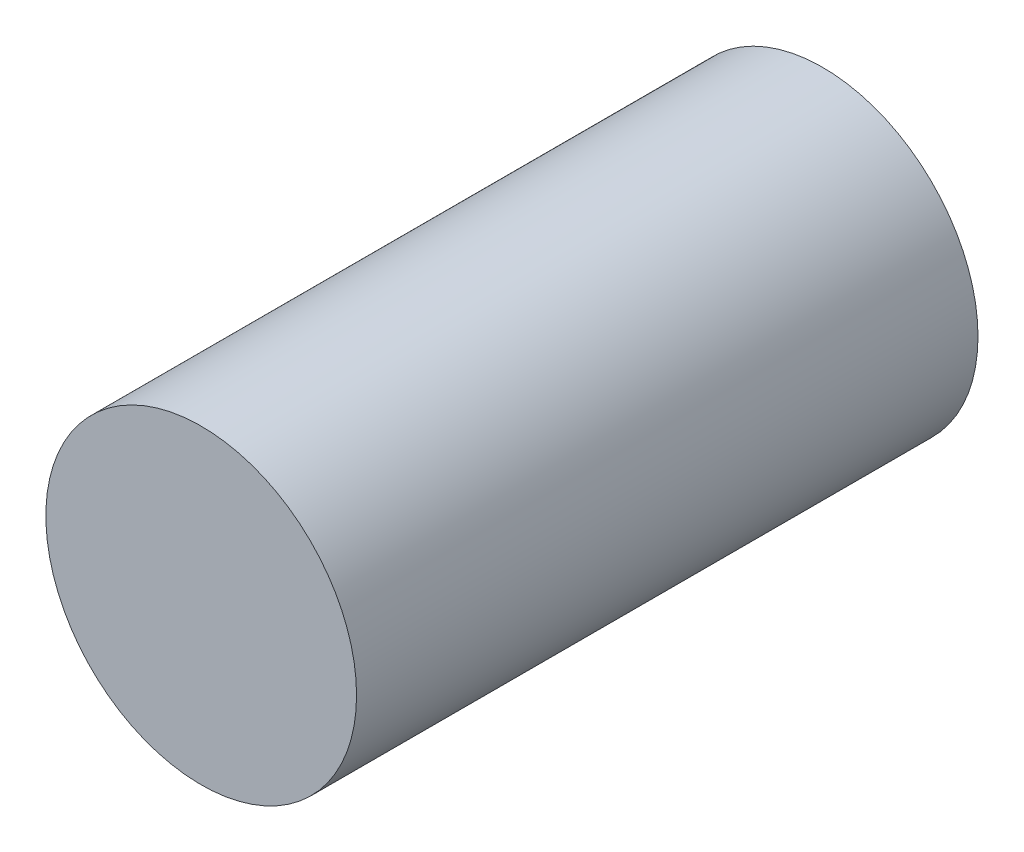
SolidWorks part; units mm, degrees
material "ABS PC"
ref_plane "Front Plane" through (0, 0, 0) normal (0, 0, 1) x (1, 0, 0)
ref_plane "Top Plane" through (0, 0, 0) normal (0, 1, 0) x (1, 0, 0)
ref_plane "Right Plane" through (0, 0, 0) normal (1, 0, 0) x (0, 0, -1)
sketch "Sketch1" plane through (0, 0, 0) normal (0, 0, 1) x (1, 0, 0)
  circle A0 centre (0, 0) radius 1.5875
  dimension "D1" = 3.175
extrude "Boss-Extrude1" add sketch "Sketch1" along normal blind 6.35
